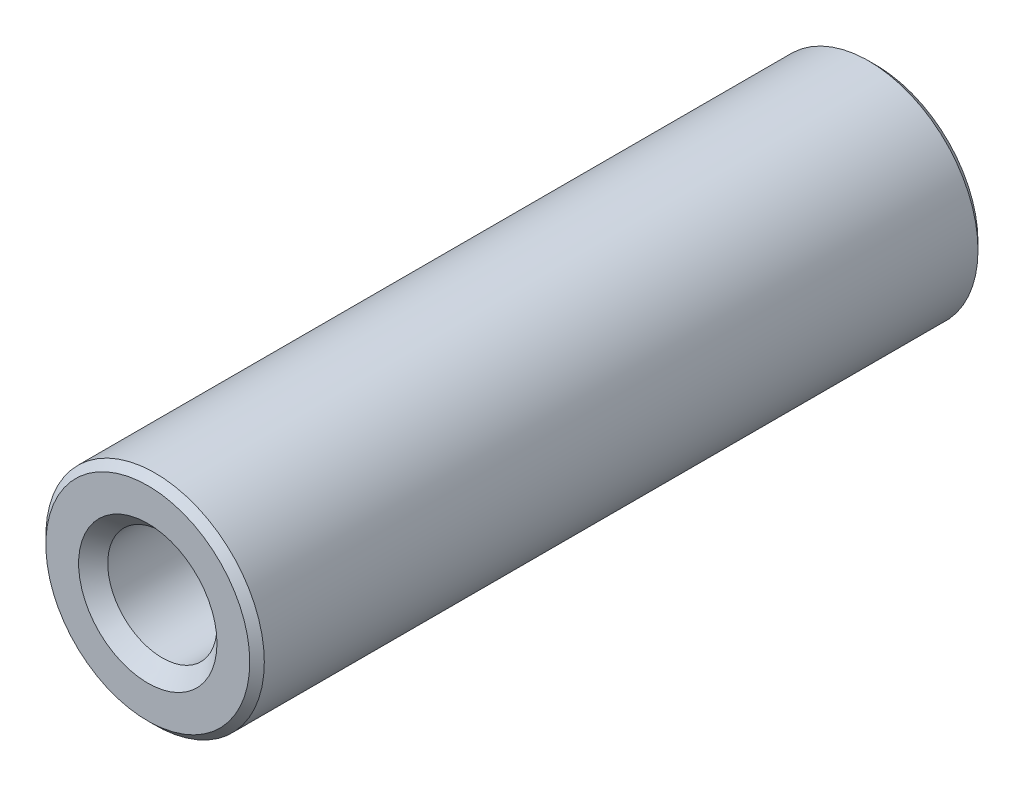
SolidWorks part; units mm, degrees
ref_plane "前视基准面" through (0, 0, 0) normal (0, 0, 1) x (1, 0, 0)
ref_plane "上视基准面" through (0, 0, 0) normal (0, 1, 0) x (1, 0, 0)
ref_plane "右视基准面" through (0, 0, 0) normal (1, 0, 0) x (0, 0, -1)
sketch "草图1" plane through (0, 0, 0) normal (0, 1, 0) x (1, 0, 0)
  line L0 (1.5, -9.3999) -> (0, -9.3999)
  line L1 (0, -9.3999) -> (0, -20.6001)
  line L2 (0, -20.6001) -> (1.5, -20.6001)
  line L3 (1.5, -20.6001) -> (1.5, -24.6001)
  line L4 (1.5, -24.6001) -> (1.8999, -25)
  line L5 (1.8999, -25) -> (2.7999, -25)
  line L6 (2.7999, -25) -> (3, -24.7999)
  line L7 (3, -24.7999) -> (3, -5.2)
  line L8 (3, -5.2) -> (2.8, -5)
  line L9 (2.8, -5) -> (1.8999, -5)
  line L10 (1.8999, -5) -> (1.5, -5.3999)
  line L11 (1.5, -5.3999) -> (1.5, -9.3999)
  line L12 (0, 25.0031) -> (0, -25) construction
  dimension "D1" = 20
  dimension "D2" = 0.9
  dimension "D3" = 135
  dimension "D4" = 45.001
  dimension "D5" = 4
  dimension "D6" = 4
  dimension "D7" = 1.5
  dimension "D8" = 0.9
  dimension "D9" = 135.001
  dimension "D10" = 135.001
  dimension "D11" = 1.5
  dimension "D12" = 0.3999
  dimension "D13" = 0.3999
revolve "旋转1" add sketch "草图1" angle 360 about L12
